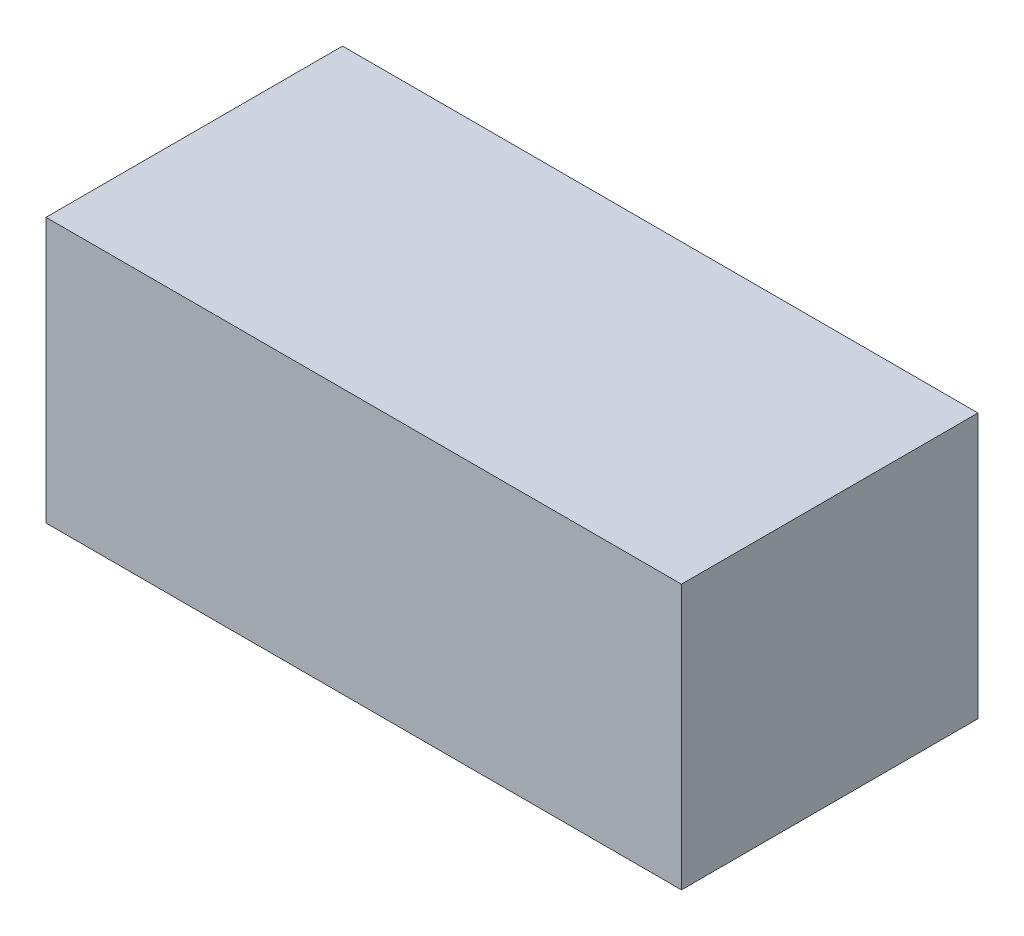
SolidWorks part; units mm, degrees
material "Plastique personnalisé"
ref_plane "Plan de face" through (0, 0, 0) normal (0, 0, 1) x (1, 0, 0)
ref_plane "Plan de dessus" through (0, 0, 0) normal (0, 1, 0) x (1, 0, 0)
ref_plane "Plan de droite" through (0, 0, 0) normal (1, 0, 0) x (0, 0, -1)
sketch "Esquisse1" plane through (0, 0, 0) normal (0, 1, 0) x (1, 0, 0)
  line L1 (-18.1351, 11.1149) -> (-13.1351, 11.1149)
  line L2 (-18.1351, 11.1149) -> (-18.1351, -16.8851)
  line L3 (-18.1351, -16.8851) -> (-13.1351, -16.8851)
  line L5 (-13.1351, -16.8851) -> (36.8649, -16.8851)
  line L9 (36.8649, -16.8851) -> (41.8649, -16.8851)
  line L11 (36.8649, 11.1149) -> (41.8649, 11.1149)
  line L12 (41.8649, -16.8851) -> (41.8649, 11.1149)
  line L13 (-13.1351, 11.1149) -> (36.8649, 11.1149)
  dimension "D1" = 5
  dimension "D3" = 5
extrude "Boss.-Extru.1" add sketch "Esquisse1" along normal blind 25 contours L11 L12 L9 L5 L3 L2 L1 L13
ref_plane "Plan1" through (41.8649, 0, 0) normal (1, 0, 0) x (0, 0, -1)
